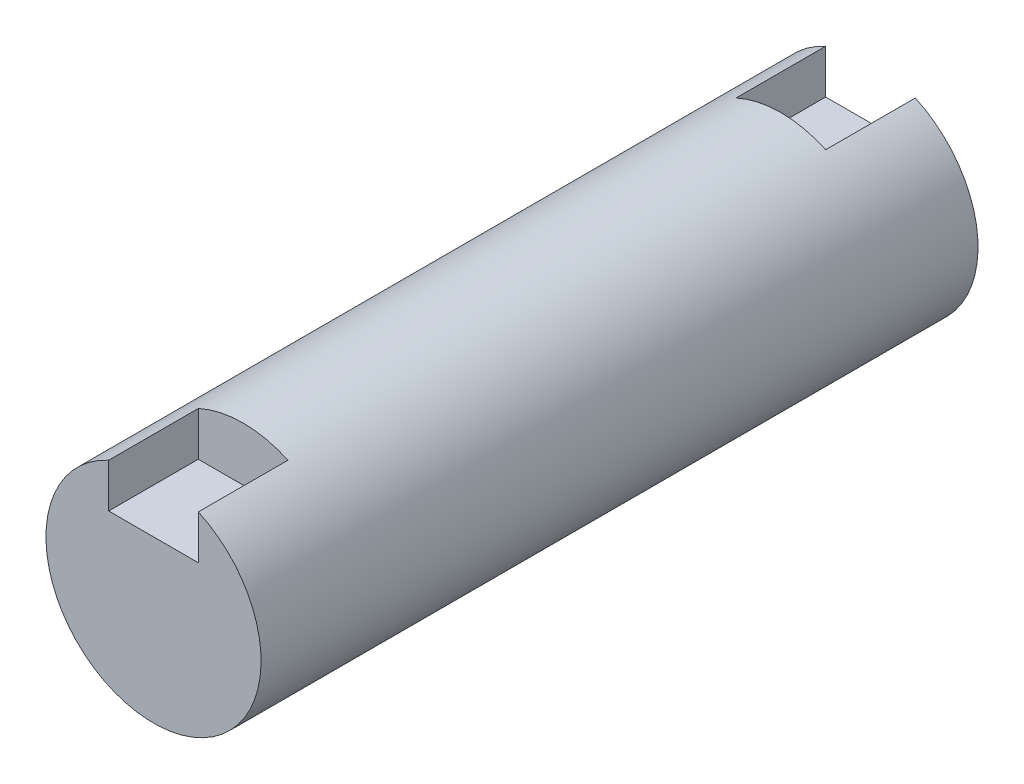
SolidWorks part; units mm, degrees
ref_plane "前视基准面" through (0, 0, 0) normal (0, 0, 1) x (1, 0, 0)
ref_plane "上视基准面" through (0, 0, 0) normal (0, 1, 0) x (1, 0, 0)
ref_plane "右视基准面" through (0, 0, 0) normal (1, 0, 0) x (0, 0, -1)
other "Configuration Table"
sketch "草图1" plane through (0, 0, 0) normal (0, 0, 1) x (1, 0, 0)
  circle A0 centre (0, 0) radius 6
  dimension "D1" = 12
extrude "凸台-拉伸1" add sketch "草图1" along normal blind 40
sketch "草图2" plane through (0, 0, 40) normal (0, 0, 1) x (1, 0, 0)
  line L0 (0, 0) -> (0, 6) construction
  line L1 (2.5, 3) -> (-2.5, 3)
  line L2 (-2.5, 3) -> (-2.5, 5.4544)
  line L3 (2.5, 3) -> (2.5, 5.4544)
  circle A0 centre (0, 0) radius 6 construction
  arc A1 (2.5, 5.4544) -> (-2.5, 5.4544) centre (0, 0) ccw
  point P10 (0, 3)
  dimension "D1" = 2.5
  dimension "D2" = 3
extrude "切除-拉伸1" cut sketch "草图2" against normal blind 5
sketch "草图3" plane through (0, 0, 0) normal (0, 0, -1) x (-1, 0, 0)
  line L0 (0, 6) -> (0, 0) construction
  line L1 (2.5, 3) -> (-2.5, 3)
  line L2 (-2.5, 3) -> (-2.5, 5.4544)
  line L3 (2.5, 3) -> (2.5, 5.4544)
  circle A0 centre (0, 0) radius 6 construction
  arc A1 (2.5, 5.4544) -> (-2.5, 5.4544) centre (0, 0) ccw
  point P9 (0, 3)
  dimension "D1" = 2.5
  dimension "D2" = 3
extrude "切除-拉伸2" cut sketch "草图3" against normal blind 5
